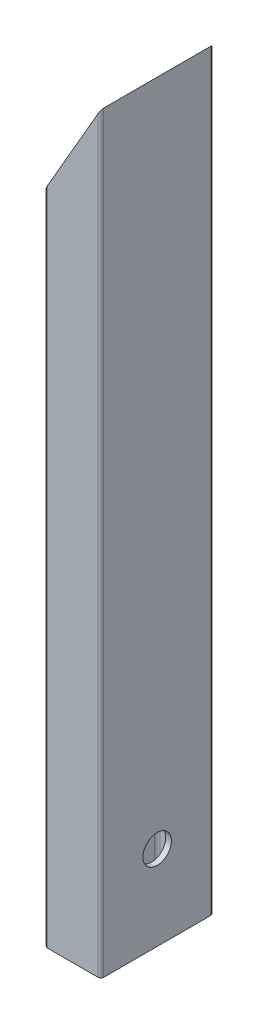
SolidWorks part; units mm, degrees
ref_plane "Plan de face" through (0, 0, 0) normal (0, 0, 1) x (1, 0, 0)
ref_plane "Plan de dessus" through (0, 0, 0) normal (0, 1, 0) x (1, 0, 0)
ref_plane "Plan de droite" through (0, 0, 0) normal (1, 0, 0) x (0, 0, -1)
sketch "Esquisse2" plane through (0, 0, 0) normal (0, 1, 0) x (1, 0, 0)
  line L0 (6, 4) -> (34, 4)
  line L1 (2, 0) -> (38, 0)
  line L2 (0, 2) -> (0, 78)
  line L3 (2, 80) -> (38, 80)
  line L4 (40, 2) -> (40, 78)
  line L5 (36, 6) -> (36, 74)
  line L6 (6, 76) -> (34, 76)
  line L7 (4, 6) -> (4, 74)
  line L8 (4, 4) -> (36, 4) construction
  line L9 (36, 4) -> (36, 76) construction
  line L10 (4, 76) -> (36, 76) construction
  line L11 (4, 4) -> (4, 76) construction
  line L12 (0, 0) -> (40, 0) construction
  line L13 (0, 0) -> (0, 80) construction
  line L14 (0, 80) -> (40, 80) construction
  line L15 (40, 0) -> (40, 80) construction
  arc A0 (34, 4) -> (36, 6) centre (34, 6) ccw
  arc A1 (36, 74) -> (34, 76) centre (34, 74) ccw
  arc A2 (6, 76) -> (4, 74) centre (6, 74) ccw
  arc A3 (4, 6) -> (6, 4) centre (6, 6) ccw
  arc A4 (2, 0) -> (0, 2) centre (2, 2) cw
  arc A5 (0, 78) -> (2, 80) centre (2, 78) cw
  arc A6 (38, 80) -> (40, 78) centre (38, 78) cw
  arc A7 (40, 2) -> (38, 0) centre (38, 2) cw
  point P24 (0, 0)
  dimension "D4" = 2
  dimension "D1" = 80
  dimension "D2" = 40
  dimension "D3" = 4
extrude "Boss.-Extru.1" add sketch "Esquisse2" along normal blind 675
sketch "Esquisse3" plane through (40, 0, 0) normal (1, 0, 0) x (0, 0, -1)
  line L0 (80, 60) -> (40, 60) construction
  line L1 (40, 60) -> (40, 0) construction
  line L2 (40, 60) -> (40, 635) construction
  line L4 (2, 0) -> (78, 0) construction
  line L5 (80, 675) -> (80, 0) construction
  circle A0 centre (40, 60) radius 10.125
  circle A1 centre (40, 635) radius 12.5
  dimension "D1" = 20.25
  dimension "D2" = 60
  dimension "D3" = 25
  dimension "D4" = 575
extrude "Enlèv. mat.-Extru.1" cut sketch "Esquisse3" against normal through all
sketch "Esquisse4" plane through (0, 0, 0) normal (0, 0, 1) x (1, 0, 0)
  line L0 (0, 675) -> (40, 675)
  line L1 (40, 675) -> (40, 535)
  line L2 (40, 675) -> (40, 0) construction
  line L3 (40, 535) -> (0, 465.718)
  line L4 (0, 675) -> (0, 0) construction
  line L5 (0, 465.718) -> (0, 675)
  line L6 (40, 535) -> (0, 535) construction
  dimension "D1" = 60
  dimension "D2" = 140
extrude "Enlèv. mat.-Extru.2" cut sketch "Esquisse4" against normal through all
